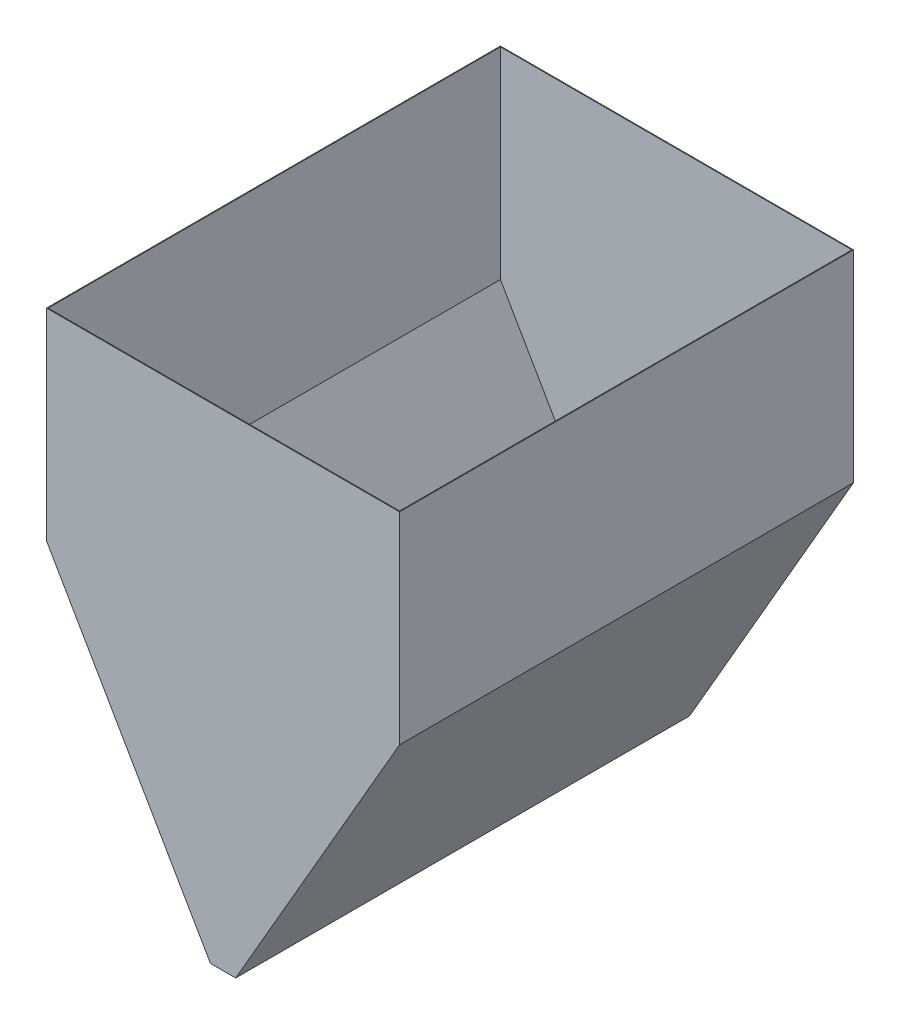
SolidWorks part; units mm, degrees
material "AISI 304"
ref_plane "Alzado" through (0, 0, 0) normal (0, 0, 1) x (1, 0, 0)
ref_plane "Planta" through (0, 0, 0) normal (0, 1, 0) x (1, 0, 0)
ref_plane "Vista lateral" through (0, 0, 0) normal (1, 0, 0) x (0, 0, -1)
sketch "Croquis1" plane through (0, 0, 0) normal (0, 1, 0) x (1, 0, 0)
  line L1 (-175, 225) -> (175, 225)
  line L2 (-175, 225) -> (-175, -225)
  line L3 (-175, -225) -> (175, -225)
  line L4 (175, 225) -> (175, -225)
  line L5 (-175, 225) -> (175, -225) construction
  line L6 (-175, -225) -> (175, 225) construction
  point P0 (0, 0)
  dimension "D1" = 350
  dimension "D2" = 450
ref_plane "Plano1" through (0, -281.458, 0) normal (0, 1, 0) x (1, 0, 0)
sketch "Croquis2" plane through (0, -281.458, 0) normal (0, 1, 0) x (1, 0, 0)
  line L1 (-12.5, 225) -> (12.5, 225)
  line L2 (-12.5, 225) -> (-12.5, -225)
  line L3 (-12.5, -225) -> (12.5, -225)
  line L4 (12.5, 225) -> (12.5, -225)
  line L5 (-12.5, 225) -> (12.5, -225) construction
  line L6 (-12.5, -225) -> (12.5, 225) construction
  line L7 (175, 225) -> (175, -225) construction
  point P0 (0, 0)
  dimension "D1" = 25
loft "Recubrir1" add profiles "Croquis1", "Croquis2"
sketch "Croquis3" plane through (0, 0, 0) normal (0, 1, 0) x (1, 0, 0)
  line L1 (-175, 225) -> (175, 225)
  line L2 (-175, 225) -> (-175, -225)
  line L3 (-175, -225) -> (175, -225)
  line L4 (175, 225) -> (175, -225)
extrude "Saliente-Extruir1" add sketch "Croquis3" along normal blind 200
shell "Vaciado2" thickness 0.76
